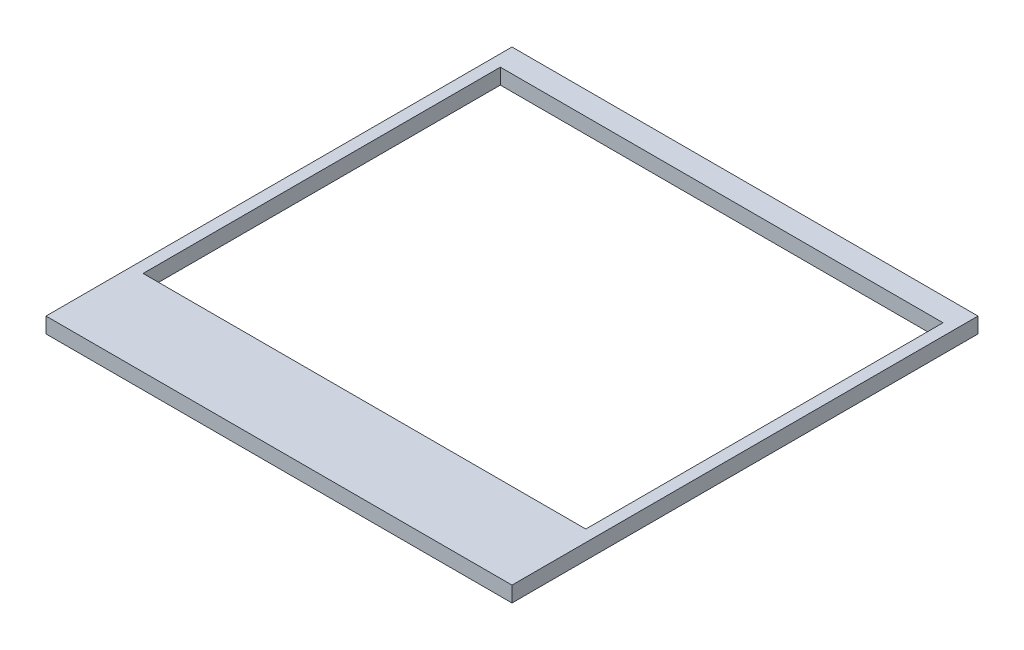
SolidWorks part; units mm, degrees
ref_plane "Front Plane" through (0, 0, 0) normal (0, 0, 1) x (1, 0, 0)
ref_plane "Top Plane" through (0, 0, 0) normal (0, 1, 0) x (1, 0, 0)
ref_plane "Right Plane" through (0, 0, 0) normal (1, 0, 0) x (0, 0, -1)
sketch "Sketch1" plane through (0, 0, 0) normal (0, 1, 0) x (1, 0, 0)
  line L1 (-38.1, -38.1) -> (38.1, -38.1)
  line L2 (-38.1, -38.1) -> (-38.1, 38.1)
  line L3 (-38.1, 38.1) -> (38.1, 38.1)
  line L4 (38.1, -38.1) -> (38.1, 38.1)
  line L5 (-38.1, -38.1) -> (38.1, 38.1) construction
  line L6 (-38.1, 38.1) -> (38.1, -38.1) construction
  point P0 (0, 0)
  dimension "D1" = 76.2
  dimension "D2" = 76.2
extrude "body" add sketch "Sketch1" along normal blind 2.54
sketch "Sketch2" plane through (0, 2.54, 0) normal (0, 1, 0) x (1, 0, 0)
  line L1 (-36.195, -24.13) -> (36.195, -24.13)
  line L2 (-36.195, -24.13) -> (-36.195, 34.29)
  line L3 (-36.195, 34.29) -> (36.195, 34.29)
  line L4 (36.195, -24.13) -> (36.195, 34.29)
  line L5 (-36.195, -24.13) -> (36.195, 34.29) construction
  line L6 (-36.195, 34.29) -> (36.195, -24.13) construction
  point P0 (0, 5.08)
  dimension "D1" = 72.39
  dimension "D2" = 0
  dimension "D3" = 58.42
  dimension "D4" = 5.08
extrude "circuitboard hole" cut sketch "Sketch2" against normal blind 2.54
